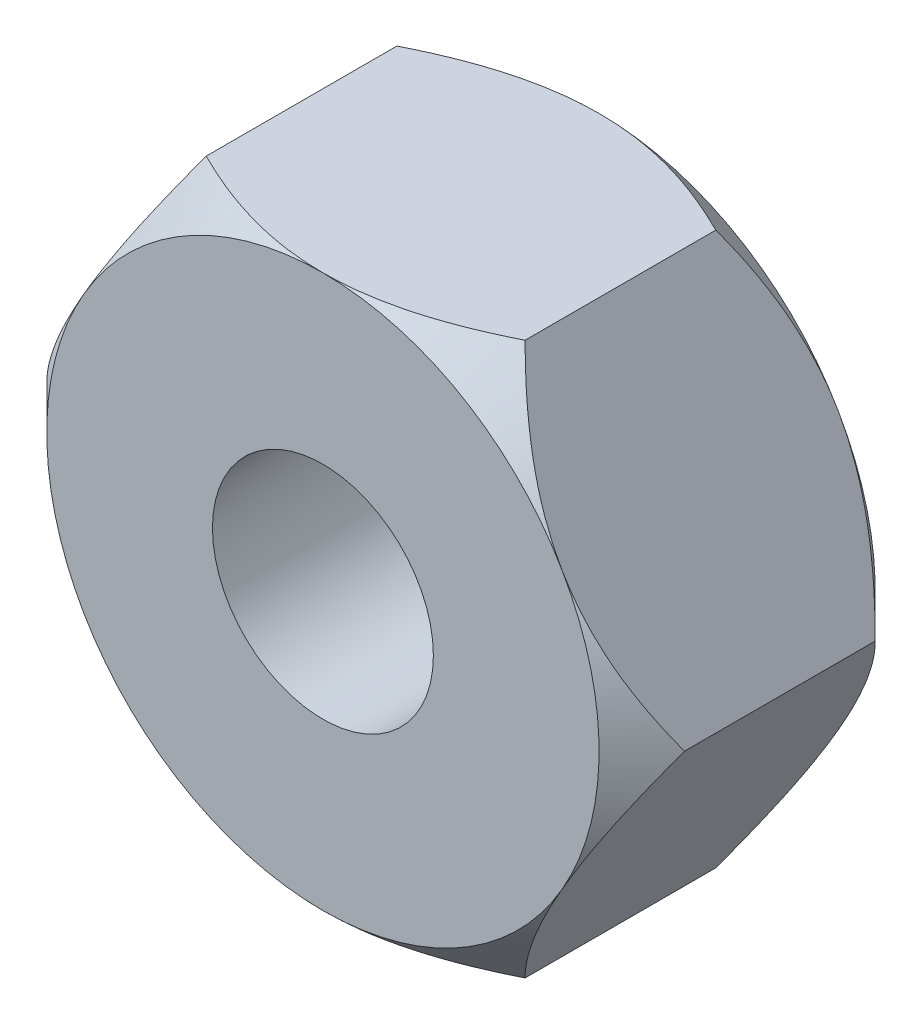
SolidWorks part; units mm, degrees
ref_plane "Ön Düzlem" through (0, 0, 0) normal (0, 0, 1) x (1, 0, 0)
ref_plane "Üst Düzlem" through (0, 0, 0) normal (0, 1, 0) x (1, 0, 0)
ref_plane "Sağ Düzlem" through (0, 0, 0) normal (1, 0, 0) x (0, 0, -1)
sketch "Çizim1" plane through (0, 0, 0) normal (0, 0, 1) x (1, 0, 0)
  line L1 (5.7735, 0) -> (2.8868, 5)
  line L2 (2.8868, 5) -> (-2.8868, 5)
  line L3 (-2.8868, 5) -> (-5.7735, 0)
  line L4 (-5.7735, 0) -> (-2.8868, -5)
  line L5 (-2.8868, -5) -> (2.8868, -5)
  line L6 (2.8868, -5) -> (5.7735, 0)
  circle A0 centre (0, 0) radius 5 construction
  circle A1 centre (0, 0) radius 2
  dimension "D2" = 4
  dimension "D1" = 10
extrude "Yükseklik-Ekstrüzyon1" add sketch "Çizim1" along normal blind 5
cosmetic thread "Kozmetik Diş Açma1" parameters "D2"=5
sketch "Çizim2" plane through (0, 0, 5) normal (0, 0, 1) x (1, 0, 0)
  circle A0 centre (0, 0) radius 5
extrude "Kes-Ekstrüzyon1" cut sketch "Çizim2" against normal blind 1 draft 45 flip side to cut
sketch "Çizim3" plane through (0, 0, 0) normal (0, 0, -1) x (-1, 0, 0)
  circle A0 centre (0, 0) radius 5
extrude "Kes-Ekstrüzyon2" cut sketch "Çizim3" against normal blind 1 draft 45 flip side to cut
